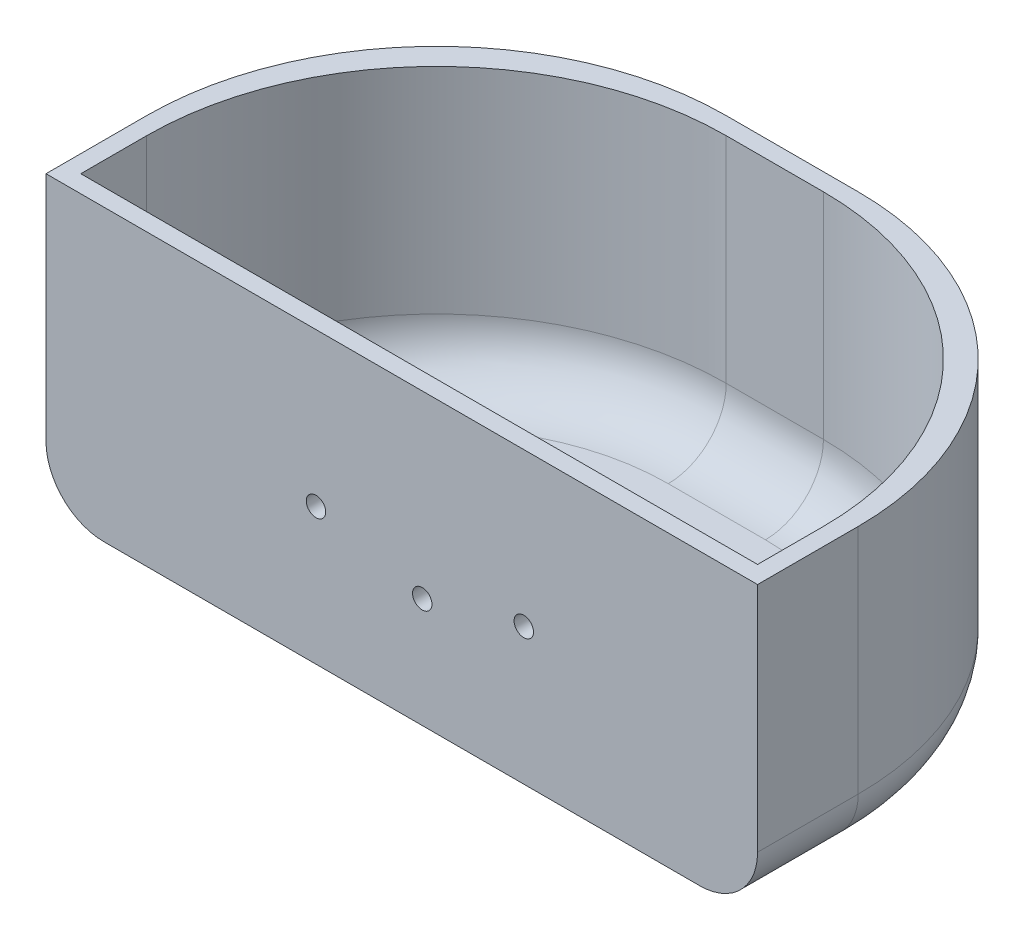
SolidWorks part; units mm, degrees
ref_plane "Front Plane" through (0, 0, 0) normal (0, 0, 1) x (1, 0, 0)
ref_plane "Top Plane" through (0, 0, 0) normal (0, 1, 0) x (1, 0, 0)
ref_plane "Right Plane" through (0, 0, 0) normal (1, 0, 0) x (0, 0, -1)
sketch "Sketch1" plane through (0, 0, 0) normal (0, 1, 0) x (1, 0, 0)
  line L1 (0, 0) -> (122.7714, 0)
  line L2 (0, 0) -> (0, 67.3648)
  line L3 (0, 67.3648) -> (122.7714, 67.3648)
  line L4 (122.7714, 0) -> (122.7714, 67.3648)
extrude "Boss-Extrude1" add sketch "Sketch1" along normal blind 50
sketch "Sketch2" plane through (0, 50, 0) normal (0, 1, 0) x (1, 0, 0)
  line L0 (0, 33.6824) -> (3, 33.6824) construction
  line L1 (0, 67.3648) -> (0, 0) construction
  line L2 (60.5151, 67.3648) -> (60.5151, 64.3648) construction
  line L3 (122.7714, 67.3648) -> (0, 67.3648) construction
  line L4 (122.7714, 33.6824) -> (119.7714, 33.6824) construction
  line L5 (122.7714, 0) -> (122.7714, 67.3648) construction
  line L6 (62.8973, 0) -> (62.8973, 3) construction
  line L7 (0, 0) -> (122.7714, 0) construction
  line L9 (3, 3) -> (119.7714, 3)
  line L10 (3, 3) -> (3, 64.3648)
  line L11 (3, 64.3648) -> (119.7714, 64.3648)
  line L12 (119.7714, 3) -> (119.7714, 64.3648)
extrude "Cut-Extrude1" cut sketch "Sketch2" against normal offset from surface (47 mm away) 3 up to face at (61.3857, 0, -33.6824)
sketch "Sketch3" plane through (0, 0, 0) normal (0, 0, 1) x (1, 0, 0)
  circle A0 centre (46.5832, 23.57) radius 1.6769
  circle A1 centre (64.9128, 18.9429) radius 1.6769
  circle A2 centre (82.4398, 23.57) radius 1.6769
extrude "Cut-Extrude3" cut sketch "Sketch3" against normal up to surface (3 mm away) up to face at (61.3857, 26.5, -3)
fillet "Fillet7" radius 50 1 edges at (119.7714, 26.5, -64.3648)
fillet "Fillet8" radius 50 1 edges at (122.7714, 25, -67.3648)
fillet "Fillet9" radius 50 1 edges at (3, 26.5, -64.3648)
fillet "Fillet10" radius 50 1 edges at (0, 25, -67.3648)
fillet "Fillet11" radius 10 5 edges at (119.7714, 3, -8.6824) (61.3857, 3, -64.3648) (105.1268, 3, -49.7202) (3, 3, -8.6824) (17.6447, 3, -49.7202)
fillet "Fillet12" radius 10 5 edges at (122.7714, 0, -8.6824) (61.3857, 0, -67.3648) (108.1268, 0, -52.7202) (0, 0, -8.6824) (14.6447, 0, -52.7202)
